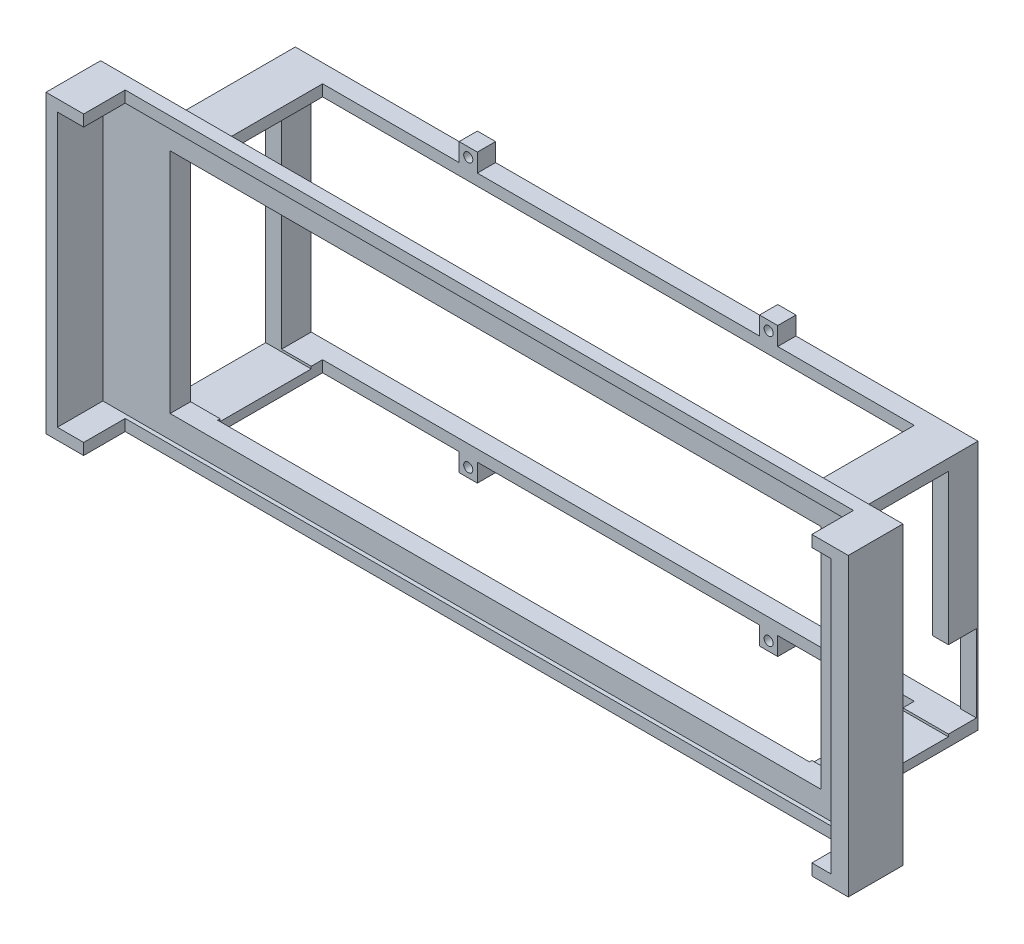
SolidWorks part; units mm, degrees
ref_plane "Front Plane" through (0, 0, 0) normal (0, 0, 1) x (1, 0, 0)
ref_plane "Top Plane" through (0, 0, 0) normal (0, 1, 0) x (1, 0, 0)
ref_plane "Right Plane" through (0, 0, 0) normal (1, 0, 0) x (0, 0, -1)
sketch "Sketch1" plane through (0, 0, 0) normal (0, 0, 1) x (1, 0, 0)
  line L1 (-73.8248, 33.403) -> (76.1752, 33.403)
  line L2 (-73.8248, 33.403) -> (-73.8248, -21.597)
  line L3 (-73.8248, -21.597) -> (76.1752, -21.597)
  line L4 (76.1752, 33.403) -> (76.1752, -21.597)
  line L5 (-73.8248, 33.403) -> (76.1752, -21.597) construction
  line L6 (-73.8248, -21.597) -> (76.1752, 33.403) construction
  line L7 (-70.3248, 30.903) -> (72.6752, 30.903)
  line L8 (-70.3248, 30.903) -> (-70.3248, -19.097)
  line L9 (-70.3248, -19.097) -> (72.6752, -19.097)
  line L10 (72.6752, 30.903) -> (72.6752, -19.097)
  line L11 (-70.3248, 30.903) -> (72.6752, -19.097) construction
  line L12 (-70.3248, -19.097) -> (72.6752, 30.903) construction
  point P0 (1.1752, 5.903)
  point P6 (1.1752, 5.903)
  dimension "D1" = 2.5
  dimension "D2" = 3.5
extrude "Boss-Extrude1" add sketch "Sketch1" along normal blind 30
sketch "Sketch2" plane through (0, 0, 30) normal (0, 0, 1) x (1, 0, 0)
  line L0 (76.1752, 33.403) -> (-73.8248, 33.403) construction
  line L1 (-83.8248, 35.903) -> (86.1752, 35.903)
  line L2 (-83.8248, 35.903) -> (-83.8248, -24.097)
  line L3 (-83.8248, -24.097) -> (86.1752, -24.097)
  line L4 (86.1752, 35.903) -> (86.1752, -24.097)
  line L5 (-83.8248, 35.903) -> (86.1752, -24.097) construction
  line L6 (-83.8248, -24.097) -> (86.1752, 35.903) construction
  line L7 (88.6752, -26.597) -> (-86.3248, -26.597)
  line L8 (88.6752, -26.597) -> (88.6752, 38.403)
  line L9 (88.6752, 38.403) -> (-86.3248, 38.403)
  line L10 (-86.3248, -26.597) -> (-86.3248, 38.403)
  line L11 (88.6752, -26.597) -> (-86.3248, 38.403) construction
  line L12 (88.6752, 38.403) -> (-86.3248, -26.597) construction
  line L13 (-73.8248, 33.403) -> (-73.8248, -21.597) construction
  point P0 (1.1752, 5.903)
  point P5 (1.1752, 5.903)
  dimension "D1" = 2.5
  dimension "D2" = 2.5
  dimension "D3" = 5
  dimension "D4" = 12.5
extrude "Cut-Extrude6" cut sketch "Sketch2" along normal blind 46 and the other way blind 1 contours L2 L1 L4 L3
sketch "Sketch3" plane through (0, 0, 29) normal (0, 0, 1) x (1, 0, 0)
  line L0 (76.1752, -21.597) -> (-73.8248, -21.597) construction
  line L1 (-87.5974, 38.403) -> (88.6752, 38.403)
  line L2 (-87.5974, 38.403) -> (-87.5974, -26.597)
  line L3 (-87.5974, -26.597) -> (88.6752, -26.597)
  line L4 (88.6752, 38.403) -> (88.6752, -26.597)
  line L5 (-87.5974, 38.403) -> (88.6752, -26.597) construction
  line L6 (-87.5974, -26.597) -> (88.6752, 38.403) construction
  line L7 (76.1752, 33.403) -> (76.1752, -21.597) construction
  point P0 (0.5389, 5.903)
  dimension "D1" = 5
  dimension "D2" = 12.5
extrude "Boss-Extrude3" add sketch "Sketch3" along normal blind 12
sketch "Sketch4" plane through (0, 0, 41) normal (0, 0, 1) x (1, 0, 0)
  line L1 (-85.0974, 35.903) -> (84.9026, 35.903)
  line L2 (-85.0974, 35.903) -> (-85.0974, -24.097)
  line L3 (-85.0974, -24.097) -> (84.9026, -24.097)
  line L4 (84.9026, 35.903) -> (84.9026, -24.097)
  line L5 (-85.0974, 35.903) -> (84.9026, -24.097) construction
  line L6 (-85.0974, -24.097) -> (84.9026, 35.903) construction
  line L8 (-87.5974, 38.403) -> (-87.5974, -26.597) construction
  line L9 (88.6752, 38.403) -> (-87.5974, 38.403) construction
  point P0 (-0.0974, 5.903)
  dimension "D1" = 2.5
  dimension "D2" = 2.5
extrude "Cut-Extrude7" cut sketch "Sketch4" against normal blind 10
sketch "Sketch5" plane through (0, 0, 31) normal (0, 0, 1) x (1, 0, 0)
  line L0 (72.6752, 30.903) -> (72.6752, -19.097) construction
  line L1 (-70.3248, -19.097) -> (72.6752, -19.097)
  line L2 (-70.3248, -19.097) -> (-70.3248, 30.903)
  line L3 (-70.3248, 30.903) -> (72.6752, 30.903)
  line L4 (72.6752, -19.097) -> (72.6752, 30.903)
  line L5 (-70.3248, -19.097) -> (72.6752, 30.903) construction
  line L6 (-70.3248, 30.903) -> (72.6752, -19.097) construction
  line L8 (-70.3248, 30.903) -> (72.6752, 30.903) construction
  point P0 (1.1752, 5.903)
  dimension "D1" = 0
  dimension "D2" = 0
extrude "Cut-Extrude8" cut sketch "Sketch5" against normal through all both and the other way through all
sketch "Sketch6" plane through (0, 0, 0) normal (0, 0, -1) x (-1, 0, 0)
  line L0 (73.8248, -21.597) -> (-76.1752, -21.597) construction
  line L1 (-32.1752, -21.597) -> (-36.1752, -21.597)
  line L2 (-32.1752, -21.597) -> (-32.1752, -25.597)
  line L3 (-32.1752, -25.597) -> (-36.1752, -25.597)
  line L4 (-36.1752, -21.597) -> (-36.1752, -25.597)
  line L5 (-32.1752, -21.597) -> (-36.1752, -25.597) construction
  line L6 (-32.1752, -25.597) -> (-36.1752, -21.597) construction
  line L7 (29.8248, -21.597) -> (33.8248, -21.597)
  line L8 (29.8248, -21.597) -> (29.8248, -25.597)
  line L9 (29.8248, -25.597) -> (33.8248, -25.597)
  line L10 (33.8248, -21.597) -> (33.8248, -25.597)
  line L11 (29.8248, -21.597) -> (33.8248, -25.597) construction
  line L12 (29.8248, -25.597) -> (33.8248, -21.597) construction
  line L13 (-36.1752, 37.403) -> (-32.1752, 37.403)
  line L14 (-36.1752, 37.403) -> (-36.1752, 33.403)
  line L15 (-36.1752, 33.403) -> (-32.1752, 33.403)
  line L16 (-32.1752, 37.403) -> (-32.1752, 33.403)
  line L17 (-36.1752, 37.403) -> (-32.1752, 33.403) construction
  line L18 (-36.1752, 33.403) -> (-32.1752, 37.403) construction
  line L19 (29.8248, 37.403) -> (33.8248, 37.403)
  line L20 (29.8248, 37.403) -> (29.8248, 33.403)
  line L21 (29.8248, 33.403) -> (33.8248, 33.403)
  line L22 (33.8248, 37.403) -> (33.8248, 33.403)
  line L23 (29.8248, 37.403) -> (33.8248, 33.403) construction
  line L24 (29.8248, 33.403) -> (33.8248, 37.403) construction
  line L25 (-76.1752, 33.403) -> (73.8248, 33.403) construction
  line L26 (73.8248, 33.403) -> (-76.1752, 33.403) construction
  line L27 (-76.1752, 33.403) -> (-76.1752, -21.597) construction
  line L28 (73.8248, 33.403) -> (73.8248, -21.597) construction
  line L30 (73.8248, -21.597) -> (73.8248, 33.403) construction
  point P0 (-34.1752, -23.597)
  point P5 (31.8248, -23.597)
  point P10 (-34.1752, 35.403)
  point P15 (31.8248, 35.403)
  dimension "D1" = 0
  dimension "D2" = 0
  dimension "D3" = 0
  dimension "D4" = 0
  dimension "D5" = 40
  dimension "D6" = 40
  dimension "D7" = 40
  dimension "D8" = 40
extrude "Boss-Extrude5" add sketch "Sketch6" against normal blind 4
sketch "Sketch7" plane through (0, 0, 0) normal (0, 0, -1) x (-1, 0, 0)
  line L0 (-32.1752, 37.403) -> (-36.1752, 37.403) construction
  line L1 (-36.1752, 37.403) -> (-36.1752, 33.403) construction
  line L2 (33.8248, 37.403) -> (29.8248, 37.403) construction
  line L3 (29.8248, 37.403) -> (29.8248, 33.403) construction
  line L4 (-36.1752, -21.597) -> (-36.1752, -25.597) construction
  line L5 (-36.1752, -25.597) -> (-32.1752, -25.597) construction
  line L6 (33.8248, -25.597) -> (33.8248, -21.597) construction
  line L7 (29.8248, -25.597) -> (33.8248, -25.597) construction
  circle A0 centre (-34.1752, 35.403) radius 1
  circle A1 centre (31.8248, 35.403) radius 1
  circle A2 centre (31.8248, -23.597) radius 1
  circle A3 centre (-34.1752, -23.597) radius 1
  dimension "D1" = 2
  dimension "D3" = 2
  dimension "D4" = 2
  dimension "D5" = 2
  dimension "D7" = 2
  dimension "D8" = 2
  dimension "D2" = 2
  dimension "D6" = 2
extrude "Cut-Extrude9" cut sketch "Sketch7" against normal blind 4 and the other way through all
sketch "Sketch8" plane through (76.1752, 0, 0) normal (1, 0, 0) x (0, 0, -1)
  line L0 (-31, -19.097) -> (0, -19.097) construction
  line L1 (-0.3566, -19.097) -> (-28.3566, -19.097)
  line L2 (-0.3566, -19.097) -> (-0.3566, -2.097)
  line L3 (-0.3566, -2.097) -> (-28.3566, -2.097)
  line L4 (-28.3566, -19.097) -> (-28.3566, -2.097)
  line L5 (-0.3566, -19.097) -> (-28.3566, -2.097) construction
  line L6 (-0.3566, -2.097) -> (-28.3566, -19.097) construction
  point P0 (-14.3566, -10.597)
  dimension "D1" = 0
extrude "Cut-Extrude12" cut sketch "Sketch8" against normal blind 10
sketch "Sketch9" plane through (0, 33.403, 0) normal (0, 1, 0) x (1, 0, 0)
  line L0 (-29.8248, -4) -> (-33.8248, -4) construction
  line L1 (-63.8248, -27.0504) -> (66.1752, -27.0504)
  line L2 (-63.8248, -27.0504) -> (-63.8248, -4)
  line L3 (-63.8248, -4) -> (66.1752, -4)
  line L4 (66.1752, -27.0504) -> (66.1752, -4)
  line L5 (-63.8248, -27.0504) -> (66.1752, -4) construction
  line L6 (-63.8248, -4) -> (66.1752, -27.0504) construction
  line L8 (76.1752, -29) -> (76.1752, 0) construction
  line L9 (-73.8248, -29) -> (-73.8248, 0) construction
  point P0 (1.1752, -15.5252)
  point P5 (1.7545, -12.7117)
  point P6 (1.3147, -16.0701)
  point P9 (-31.8248, -4)
  dimension "D1" = 0
  dimension "D2" = 10
  dimension "D3" = 10
extrude "Cut-Extrude13" cut sketch "Sketch9" against normal blind 72
sketch "Sketch10" plane through (-73.8248, 0, 0) normal (-1, 0, 0) x (0, 0, 1)
  line L1 (26.5, -19.6104) -> (6.5, -19.6104)
  line L2 (26.5, -19.6104) -> (26.5, 30.903)
  line L3 (26.5, 30.903) -> (6.5, 30.903)
  line L4 (6.5, -19.6104) -> (6.5, 30.903)
  line L5 (26.5, -19.6104) -> (6.5, 30.903) construction
  line L6 (26.5, 30.903) -> (6.5, -19.6104) construction
  line L9 (29, -21.597) -> (29, 33.403) construction
  line L12 (29, 33.403) -> (0, 33.403) construction
  point P0 (16.5, 5.6463)
  point P5 (16.348, 8.3229)
  point P7 (18.2347, 8.487)
  dimension "D1" = 20
  dimension "D2" = 2.5
  dimension "D3" = 2.5
extrude "Cut-Extrude14" cut sketch "Sketch10" against normal blind 177
sketch "Sketch11" plane through (0, 38.403, 0) normal (0, 1, 0) x (1, 0, 0)
  line L1 (80.6752, -42.5262) -> (-79.3248, -42.5262)
  line L2 (80.6752, -42.5262) -> (80.6752, -31.8683)
  line L3 (80.6752, -31.8683) -> (-79.3248, -31.8683)
  line L4 (-79.3248, -42.5262) -> (-79.3248, -31.8683)
  line L5 (80.6752, -42.5262) -> (-79.3248, -31.8683) construction
  line L6 (80.6752, -31.8683) -> (-79.3248, -42.5262) construction
  line L8 (88.6752, -41) -> (88.6752, -29) construction
  point P0 (0.6752, -37.1972)
  point P5 (-0.5755, -37.1972)
  point P8 (80.6752, -37.1972)
  dimension "D1" = 160
  dimension "D2" = 8
extrude "Cut-Extrude15" cut sketch "Sketch11" against normal blind 177
